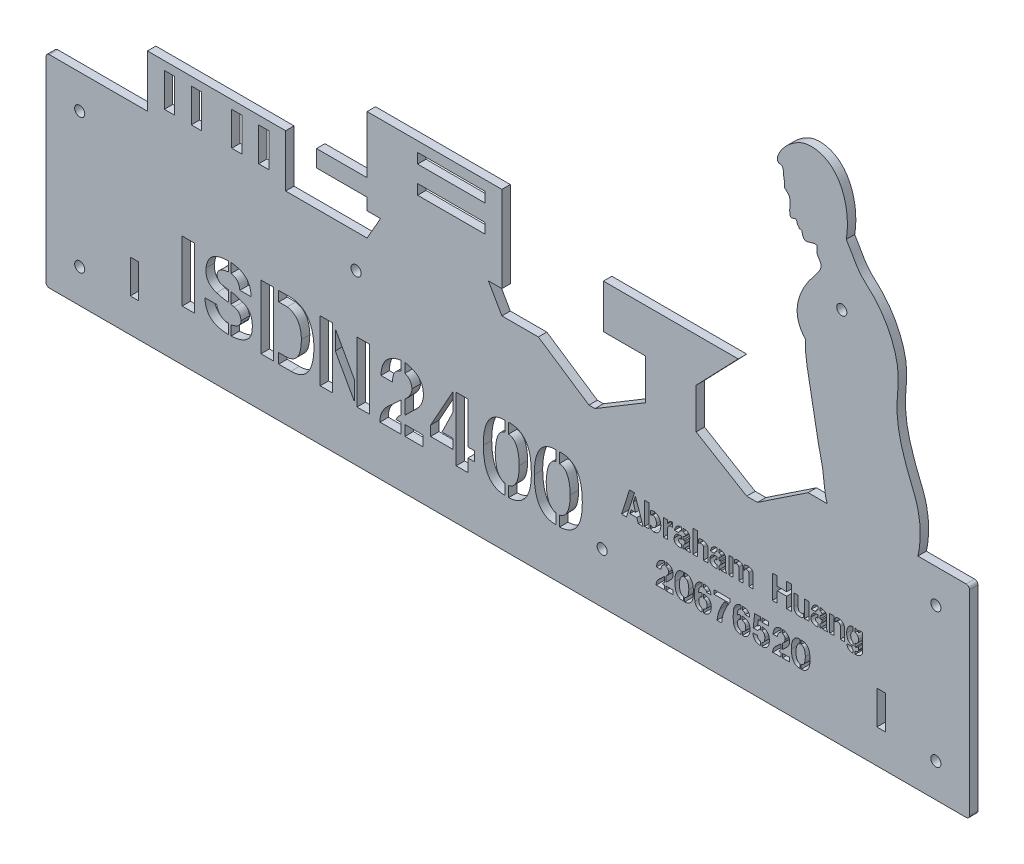
SolidWorks part; units mm, degrees
ref_plane "前视基准面" through (0, 0, 0) normal (0, 0, 1) x (1, 0, 0)
ref_plane "上视基准面" through (0, 0, 0) normal (0, 1, 0) x (1, 0, 0)
ref_plane "右视基准面" through (0, 0, 0) normal (1, 0, 0) x (0, 0, -1)
sketch "草图1" plane through (0, 0, 0) normal (0, 0, 1) x (1, 0, 0)
  line L0 (-63.75, 0) -> (0, 0) construction
  line L1 (-280, 150) -> (20, 150)
  line L2 (-280, 150) -> (-280, -50)
  line L3 (-280, -50) -> (20, -50)
  line L4 (20, 150) -> (20, -50)
  line L5 (-63.75, 0) -> (-9.4828, 19.7517) construction
  circle A0 centre (-9.4828, 19.7517) radius 1.5
  circle A1 centre (-27.9161, 61.985) radius 1.5
  circle A2 centre (-5.7494, 42.7517) radius 1.5
  point P0 (0, 0)
  point P12 (-63.75, 0)
  dimension "D3" = 3
  dimension "D4" = 42.2333
  dimension "D5" = 18.4333
  dimension "D6" = 22.1667
  dimension "D7" = 23
  dimension "D8" = 63.75
  dimension "D1" = 300
  dimension "D2" = 200
  dimension "D9" = 57.75
  dimension "D10" = 20
  dimension "D11" = 50
  dimension "D12" = 20
extrude "凸台-拉伸1" add sketch "草图1" along normal blind 2.5
sketch "草图2" plane through (0, 0, 2.5) normal (0, 0, 1) x (1, 0, 0)
  line L1 (-280, -50) -> (20, -50) construction
  circle A0 centre (-63.75, 0) radius 1.5
  circle A1 centre (-9.4828, 19.7517) radius 1.5 construction
  dimension "D1" = 63.75
  dimension "D2" = 50
extrude "切除-拉伸1" cut sketch "草图2" against normal through all
sketch "草图3" plane through (0, 0, 2.5) normal (0, 0, 1) x (1, 0, 0)
  line L0 (-280, -50) -> (20, -50) construction
  circle A0 centre (-133.4032, -15) radius 2
  circle A1 centre (-63.75, 0) radius 1.5 construction
  circle A2 centre (-213.4032, -10) radius 2
  dimension "D1" = 4
  dimension "D2" = 71.25
  dimension "D3" = 35
  dimension "D4" = 5
  dimension "D5" = 80
extrude "切除-拉伸2" cut sketch "草图3" against normal through all
sketch "草图4" plane through (0, 0, 2.5) normal (0, 0, 1) x (1, 0, 0)
  line L0 (-213.4032, 93.9226) -> (-213.4032, -10) construction
  line L1 (-223.4032, 111.2388) -> (-223.4032, 26.2684) construction
  line L2 (-203.4032, 111.2388) -> (-203.4032, 26.2684) construction
  line L4 (-225.9032, 13) -> (-220.9032, 13) construction
  line L5 (-225.9032, 13) -> (-225.9032, 53) construction
  line L6 (-225.9032, 53) -> (-220.9032, 53) construction
  line L7 (-220.9032, 13) -> (-220.9032, 53) construction
  line L8 (-225.9032, 13) -> (-220.9032, 53) construction
  line L9 (-225.9032, 53) -> (-220.9032, 13) construction
  line L13 (-220.9032, 13) -> (-217.9032, 13)
  line L14 (-225.9032, 23) -> (-228.9032, 23)
  line L15 (-225.9032, 23) -> (-225.9032, 13)
  line L16 (-225.9032, 13) -> (-228.9032, 13)
  line L17 (-228.9032, 23) -> (-228.9032, 13)
  line L18 (-217.9032, 23) -> (-217.9032, 13)
  line L19 (-220.9032, 23) -> (-217.9032, 23)
  line L20 (-220.9032, 23) -> (-220.9032, 13)
  line L21 (-205.9032, 23) -> (-205.9032, 13)
  line L22 (-205.9032, 23) -> (-208.9032, 23)
  line L23 (-208.9032, 23) -> (-208.9032, 13)
  line L24 (-205.9032, 13) -> (-208.9032, 13)
  line L25 (-200.9032, 13) -> (-197.9032, 13)
  line L26 (-197.9032, 23) -> (-197.9032, 13)
  line L27 (-200.9032, 23) -> (-197.9032, 23)
  line L28 (-200.9032, 23) -> (-200.9032, 13)
  circle A2 centre (-213.4032, -10) radius 2 construction
  point P4 (-213.4032, -10)
  point P12 (-223.4032, 33)
  dimension "D5" = 23
  dimension "D1" = 10
  dimension "D2" = 5
  dimension "D3" = 40
  dimension "D4" = 3
  dimension "D6" = 10
extrude "切除-拉伸3" cut sketch "草图4" against normal through all
sketch "草图5" plane through (0, 0, 2.5) normal (0, 0, 1) x (1, 0, 0)
  line L0 (-280, 50) -> (20, 50) construction
  line L3 (-280, 150) -> (-280, -50) construction
  line L4 (20, -50) -> (20, 150) construction
  line L5 (-280, 42.5) -> (-128.75, 42.5)
  line L7 (-225.9032, 23) -> (-228.9032, 23) construction
  line L9 (-5.3703, 10) -> (31.4502, 10)
  line L10 (20, 150) -> (-280, 150)
  line L11 (-280, 150) -> (-280, 42.5)
  line L14 (-350.0387, -283.3449) -> (180.373, -227.5964) construction
  line L17 (-35.2411, 74.8072) -> (-26.5966, 80.6857)
  line L18 (-26.8206, 6.8426) -> (-5.682, 8.692)
  line L22 (-35.2469, 75.2955) -> (-26.9945, 81.3126)
  line L24 (-5.3703, 10) -> (-128.75, 10)
  line L25 (-128.75, 10) -> (-128.75, 42.5)
  line L26 (20, 150) -> (-280, 150) construction
  line L27 (20, 150) -> (20, 10)
  line L28 (20, 10) -> (31.4502, 10)
  circle A0 centre (-63.75, 0) radius 1.5 construction
  spline S2 degree 3 poles (-35.2411, 74.8072) (-35.8907, 75.2025) (-36.9785, 74.58) (-39.1322, 74.1589) (-39.6333, 75.4863) (-39.7485, 76.6552) (-40.7028, 76.4112) (-40.6109, 77.1132) (-41.0283, 77.0822) (-41.3185, 78.5541) (-41.8186, 78.5631) (-42.6818, 78.0888) (-43.3106, 78.2933) (-43.3714, 79.7422) (-43.3597, 80.2486) (-43.1317, 83.4149) (-44.2606, 84.2468) (-45.0788, 84.9907) (-44.8149, 85.529) (-44.872, 86.6167) (-45.3572, 87.956) (-45.1251, 90.1779) (-46.6801, 90.3339) (-47.4824, 91.3508) (-45.629, 94.7067) (-43.0484, 97.1852) (-38.7822, 99.9549) (-27.7554, 98.5587) (-25.4098, 87.3129) (-26.5966, 80.6857) knots 0 0 0 0 0.043193 0.064097 0.091202 0.100429 0.112327 0.119288 0.126513 0.131605 0.149013 0.160158 0.174274 0.188894 0.224193 0.256574 0.280334 0.294839 0.303662 0.313259 0.344032 0.378992 0.393153 0.405387 0.468199 0.523468 0.594118 0.70076 1 1 1 1
  spline S3 degree 3 poles (-35.2469, 75.2955) (-35.1817, 74.5171) (-35.7196, 72.678) (-33.3259, 70.4782) (-35.135, 67.709) (-39.9597, 62.0648) (-43.4588, 54.1346) (-38.752, 49.1471) knots 0 0 0 0 0.086993 0.176837 0.283184 0.373621 1 1 1 1
  spline S4 degree 3 poles (-38.752, 49.1471) (-38.8956, 44.3564) (-36.8489, 36.7379) (-35.4548, 25.7834) (-32.5352, 15.9422) (-33.1127, 6.6584) (-26.8206, 6.8426) knots 0 0 0 0 0.308241 0.511644 0.709109 1 1 1 1
  spline S5 degree 3 poles (-26.9945, 81.3126) (-25.1346, 78.8034) (-23.6052, 74.5985) (-17.3042, 69.4695) (-12.9955, 62.9352) (-10.5649, 53.5275) (-12.1282, 44.5336) (-10.5426, 36.4726) (-8.4913, 30.4751) (-6.8804, 26.7263) (-4.2667, 19.9227) (-4.2801, 13.4665) (-5.682, 8.692) knots 0 0 0 0 0.120883 0.161371 0.308806 0.411578 0.52584 0.652386 0.720933 0.768717 0.80852 1 1 1 1
  dimension "D1" = 19.5
  dimension "D5" = 40
  dimension "D6" = 65
extrude "切除-拉伸4-人" cut sketch "草图5" against normal blind 10
sketch "草图12" plane through (0, 0, 2.5) normal (0, 0, 1) x (1, 0, 0)
  line L0 (-143.75, 31.5) -> (-143.75, 28.5) construction
  line L1 (-153.75, 31.5) -> (-133.75, 31.5)
  line L2 (-153.75, 31.5) -> (-153.75, 28.5)
  line L3 (-153.75, 28.5) -> (-133.75, 28.5)
  line L4 (-133.75, 31.5) -> (-133.75, 28.5)
  line L5 (-170.9683, 34) -> (-132.8548, 34) construction
  line L6 (-153.75, 30) -> (-133.75, 30) construction
  line L7 (-153.75, 39.5) -> (-133.75, 39.5)
  line L8 (-133.75, 36.5) -> (-133.75, 39.5)
  line L9 (-153.75, 36.5) -> (-133.75, 36.5)
  line L10 (-153.75, 36.5) -> (-153.75, 39.5)
  circle A0 centre (-63.75, 0) radius 1.5 construction
  dimension "D2" = 30
  dimension "D1" = 80
  dimension "D3" = 20
  dimension "D4" = 3
  dimension "D5" = 5
extrude "切除-拉伸8" cut sketch "草图12" against normal through all
sketch "草图18" plane through (0, 0, 2.5) normal (0, 0, 1) x (1, 0, 0)
  circle A0 centre (-63.75, 0) radius 1.5
  circle A1 centre (-63.75, 0) radius 1.5 construction
extrude "凸台-拉伸5" add sketch "草图18" against normal up to surface (2.5 mm away) up to face at (-143.75, 30, 0)
sketch "草图7" plane through (0, 0, 2.5) normal (0, 0, 1) x (1, 0, 0)
  line L0 (-77.9161, 61.3532) -> (-77.9161, -32.2635) construction
  line L1 (-117.9161, 10) -> (-102.9161, 0)
  line L2 (-32.2146, 10) -> (-128.75, 10) construction
  line L3 (-102.9161, 0) -> (-52.9161, 0)
  line L4 (-37.9161, 10) -> (-52.9161, 0)
  line L5 (-117.9161, 10) -> (-37.9161, 10)
  circle A0 centre (-27.9161, 61.985) radius 1.5 construction
  dimension "D1" = 50
  dimension "D2" = 80
  dimension "D3" = 50
  dimension "D4" = 10
extrude "切除-拉伸5" cut sketch "草图7" against normal through all
sketch "草图6" plane through (0, 0, 0) normal (0, 0, 1) x (1, 0, 0)
  line L0 (-101.1283, 0) -> (-86.1283, 9)
  line L1 (-102.9161, 0) -> (-52.9161, 0) construction
  line L2 (-86.1283, 9) -> (-86.1283, 21)
  line L3 (-86.1283, 21) -> (-98.6283, 21)
  line L4 (-98.6283, 21) -> (-98.6283, 34)
  line L5 (-98.6283, 34) -> (-58.6283, 34)
  line L6 (-58.6283, 34) -> (-71.1283, 21)
  line L7 (-71.1283, 21) -> (-71.1283, 9)
  line L8 (-71.1283, 9) -> (-56.1283, 0)
  line L9 (-101.1283, 0) -> (-56.1283, 0)
  line L10 (-78.6283, 44.1613) -> (-78.6283, -37.7704) construction
  dimension "D1" = 45
  dimension "D3" = 15
  dimension "D4" = 34
  dimension "D5" = 13
  dimension "D6" = 12
  dimension "D7" = 20
  dimension "D8" = 20
extrude "凸台-拉伸2" add sketch "草图6" along normal up to surface (2.5 mm away) up to face at (-82.9174, 20.9666, 2.5)
sketch "草图8" plane through (0, 0, 2.5) normal (0, 0, 1) x (1, 0, 0)
  line L0 (-280, 42.5) -> (-128.75, 42.5) construction
  line L2 (-168.75, 42.5) -> (-168.75, 10)
  line L3 (-168.75, 10) -> (-192.9032, 10)
  line L5 (-128.75, 10) -> (-128.75, 42.5) construction
  line L7 (-192.9032, 10) -> (-192.9032, 25.5)
  line L8 (-192.9032, 25.5) -> (-233.9032, 25.5)
  line L9 (-233.9032, 25.5) -> (-233.9032, 10)
  line L10 (-233.9032, 10) -> (-280, 10)
  line L11 (-280, 42.5) -> (-280, -50) construction
  line L12 (-280, 10) -> (-280, 42.5)
  line L13 (-280, 42.5) -> (-168.75, 42.5)
  line L14 (-117.9161, 10) -> (-128.75, 10) construction
  line L15 (-197.9032, 23) -> (-200.9032, 23) construction
  line L16 (-213.4032, 25.5) -> (-213.4032, 8.1583) construction
  line L17 (-208.9032, 23) -> (-208.9032, 13) construction
  line L18 (-217.9032, 13) -> (-217.9032, 23) construction
  line L19 (-197.9032, 13) -> (-197.9032, 23) construction
  dimension "D1" = 2.5
  dimension "D2" = 40
  dimension "D3" = 5
extrude "切除-拉伸6" cut sketch "草图8" against normal through all
sketch "草图9" plane through (0, 0, 2.5) normal (0, 0, 1) x (1, 0, 0)
  line L0 (-148.75, 42.5) -> (-148.75, 10) construction
  line L1 (-168.75, 42.5) -> (-128.75, 42.5) construction
  line L2 (-168.75, 17) -> (-164.75, 17)
  line L3 (-168.75, 10) -> (-168.75, 42.5) construction
  line L4 (-164.75, 17) -> (-168.75, 10)
  line L5 (-168.75, 10) -> (-168.75, 17)
  line L6 (-132.75, 17) -> (-128.75, 10)
  line L7 (-128.75, 10) -> (-128.75, 17)
  line L8 (-128.75, 17) -> (-132.75, 17)
  dimension "D1" = 7
  dimension "D2" = 4
extrude "切除-拉伸7" cut sketch "草图9" against normal through all
sketch "草图10" plane through (0, 0, 2.5) normal (0, 0, 1) x (1, 0, 0)
  line L0 (-168.75, 17) -> (-168.75, 42.5) construction
  line L1 (-168.75, 25.5) -> (-183.75, 25.5)
  line L2 (-168.75, 25.5) -> (-168.75, 20.5)
  line L3 (-168.75, 20.5) -> (-183.75, 20.5)
  line L4 (-183.75, 25.5) -> (-183.75, 20.5)
  line L5 (-164.75, 17) -> (-168.75, 17) construction
  dimension "D1" = 15
  dimension "D2" = 5
  dimension "D3" = 3.5
extrude "凸台-拉伸3" add sketch "草图10" against normal up to surface (2.5 mm away) up to face at (-143.75, 30, 0)
sketch "草图11" plane through (0, 0, 2.5) normal (0, 0, 1) x (1, 0, 0)
  circle A0 centre (-213.4032, -10) radius 2
  circle A1 centre (-133.4032, -15) radius 2
  circle A2 centre (-9.4828, 19.7517) radius 1.5
extrude "凸台-拉伸4" add sketch "草图11" against normal up to surface (2.5 mm away) up to face at (-143.75, 30, 0)
sketch "草图13" plane through (0, 0, 2.5) normal (0, 0, 1) x (1, 0, 0)
  line L0 (-280, 10) -> (-233.9032, 10) construction
  line L1 (-280, -50) -> (-264, -50)
  line L2 (-280, -50) -> (-280, 10)
  line L3 (-280, 10) -> (-264, 10)
  line L4 (-264, -50) -> (-264, 10)
  dimension "D1" = 16
extrude "切除-拉伸9" cut sketch "草图13" against normal through all
sketch "草图19" plane through (0, 0, 2.5) normal (0, 0, 1) x (1, 0, 0)
  line L1 (20, -50) -> (10, -50)
  line L2 (20, -50) -> (20, 10)
  line L3 (20, 10) -> (10, 10)
  line L4 (10, -50) -> (10, 10)
  dimension "D1" = 10
extrude "切除-拉伸14" cut sketch "草图19" against normal through all
sketch "草图14" plane through (0, 0, 2.5) normal (0, 0, 1) x (1, 0, 0)
  line L0 (-127, -50) -> (-127, 72.7427) construction
  line L1 (-264, -50) -> (10, -50) construction
  line L2 (-264, -20) -> (10, -20) construction
  line L3 (-264, -50) -> (-264, 10) construction
  line L5 (10, 10) -> (10, -50) construction
  circle A0 centre (-254, 0) radius 1.5
  circle A1 centre (-254, -40) radius 1.5
  circle A2 centre (0, -40) radius 1.5
  circle A3 centre (0, 0) radius 1.5
  circle A4 centre (-172, 0) radius 1.5
  circle A5 centre (-99, -35) radius 1.5
  point P8 (10, -20)
  dimension "D1" = 3
  dimension "D2" = 20
  dimension "D4" = 20
  dimension "D5" = 45
  dimension "D6" = 15
  dimension "D7" = 28
  dimension "D3" = 10
extrude "切除-拉伸10" cut sketch "草图14" against normal through all
sketch "草图15" plane through (0, 0, 2.5) normal (0, 0, 1) x (1, 0, 0)
  line L0 (-127, -50) -> (-127, 10) construction
  line L1 (-264, -50) -> (10, -50) construction
  line L2 (-117.9161, 10) -> (-128.75, 10) construction
  line L3 (-264, -50) -> (-264, 10) construction
  line L4 (-239, -40) -> (-236.5, -40)
  line L5 (-239, -40) -> (-239, -30)
  line L6 (-239, -30) -> (-236.5, -30)
  line L7 (-236.5, -40) -> (-236.5, -30)
  line L8 (-15, -30) -> (-17.5, -30)
  line L9 (-17.5, -40) -> (-17.5, -30)
  line L10 (-15, -40) -> (-17.5, -40)
  line L11 (-15, -40) -> (-15, -30)
  line L12 (-239, -35) -> (-236.5, -35) construction
  dimension "D1" = 2.5
  dimension "D2" = 10
  dimension "D3" = 25
  dimension "D4" = 15
extrude "切除-拉伸11" cut sketch "草图15" against normal through all
fillet "圆角1" radius 1 4 edges at (-264, -50, 1.25) (-264, 10, 1.25) (10, -50, 1.25) (10, 10, 1.25)
sketch "草图16" plane through (0, 0, 2.5) normal (0, 0, 1) x (1, 0, 0)
  text T0 "ISDN2400" font "Font Creator Program" height 18
extrude "切除-拉伸12" cut sketch "草图16" against normal through all
sketch "草图17" plane through (0, 0, 2.5) normal (0, 0, 1) x (1, 0, 0)
  text T0 "Abraham Huang\r\n  20676520\r\n" font "Font Creator Program" height 7
extrude "切除-拉伸13" cut sketch "草图17" against normal through all
sketch "草图20" plane through (0, 0, 0) normal (0, 0, 1) x (1, 0, 0)
  line L0 (-64.8664, -17.3396) -> (-64.2982, -17.3396)
  line L1 (-75.5238, -17.3285) -> (-74.9556, -17.3285)
  line L2 (-75.5238, -17.3285) -> (-75.5238, -23.3766)
  line L3 (-75.5238, -23.3766) -> (-74.9556, -23.3766)
  line L4 (-74.9556, -17.3285) -> (-74.9556, -23.3766)
  line L5 (-64.8664, -17.3396) -> (-64.8664, -23.3877)
  line L6 (-64.8664, -23.3877) -> (-64.2982, -23.3877)
  line L7 (-64.2982, -17.3396) -> (-64.2982, -23.3877)
  line L8 (-34.8962, -17.3695) -> (-34.3281, -17.3695)
  line L9 (-34.8962, -17.3695) -> (-34.8962, -23.4176)
  line L10 (-34.8962, -23.4176) -> (-34.3281, -23.4176)
  line L11 (-34.3281, -17.3695) -> (-34.3281, -23.4176)
  line L12 (-24.5738, -17.3025) -> (-23.9451, -17.3025)
  line L13 (-24.5738, -17.3025) -> (-24.5738, -24.8785)
  line L14 (-24.5738, -24.8785) -> (-23.9451, -24.8785)
  line L15 (-23.9451, -17.3025) -> (-23.9451, -24.8785)
  line L16 (-85.105, -14.9114) -> (-84.6278, -14.9114)
  line L17 (-85.105, -14.9114) -> (-85.105, -23.4007)
  line L18 (-85.105, -23.4007) -> (-84.6278, -23.4007)
  line L19 (-84.6278, -14.9114) -> (-84.6278, -23.4007)
  line L20 (-85.105, -22.8989) -> (-85.105, -16.2027) construction
  point P16 (-23.9451, -17.3025)
  point P23 (-84.6278, -23.4007)
extrude "凸台-拉伸6" add sketch "草图20" along normal up to surface (2.5 mm away) up to face at (-24.8991, -20.1082, 2.5)
